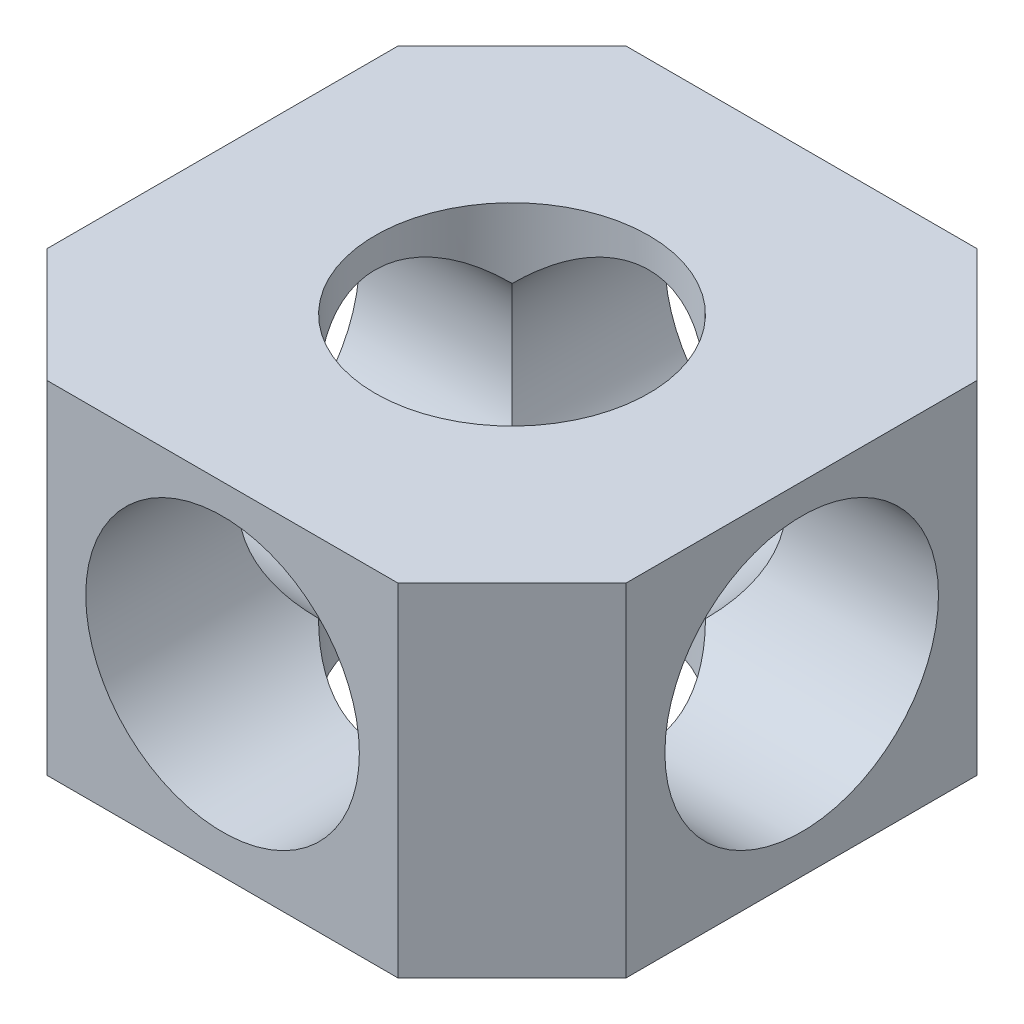
SolidWorks part; units mm, degrees
ref_plane "Front Plane" through (0, 0, 0) normal (0, 0, 1) x (1, 0, 0)
ref_plane "Top Plane" through (0, 0, 0) normal (0, 1, 0) x (1, 0, 0)
ref_plane "Right Plane" through (0, 0, 0) normal (1, 0, 0) x (0, 0, -1)
sketch "Sketch1" plane through (0, 0, 0) normal (0, 1, 0) x (1, 0, 0)
  line L1 (-5.6046, 5.0044) -> (2.862, 5.0044)
  line L2 (-5.6046, 5.0044) -> (-5.6046, -3.4623)
  line L3 (-5.6046, -3.4623) -> (2.862, -3.4623)
  line L4 (2.862, 5.0044) -> (2.862, -3.4623)
  line L5 (-5.6046, 5.0044) -> (2.862, -3.4623) construction
  line L6 (-5.6046, -3.4623) -> (2.862, 5.0044) construction
  point P0 (-1.3713, 0.7711)
  dimension "D1" = 8.4667
extrude "Boss-Extrude1" add sketch "Sketch1" along normal blind 5
chamfer "Chamfer1" distance 1.6667 4 edges at (-5.6046, 2.5, -5.0044) (2.862, 2.5, -5.0044) (-5.6046, 2.5, 3.4623) (2.862, 2.5, 3.4623)
sketch "Sketch2" plane through (2.862, 0, 0) normal (1, 0, 0) x (0, 0, -1)
  line L4 (-1.7956, 0) -> (3.3377, 0)
  line L5 (3.3377, 0) -> (3.3377, 5)
  line L6 (3.3377, 5) -> (-1.7956, 5)
  line L7 (-1.7956, 5) -> (-1.7956, 0)
  line L8 (-1.7956, 0) -> (3.3377, 0)
  line L9 (3.3377, 0) -> (3.3377, 5)
  line L10 (3.3377, 5) -> (-1.7956, 5)
  line L11 (-1.7956, 5) -> (-1.7956, 0)
  circle A0 centre (0.7727, 2.565) radius 2
  dimension "D4" = 4
  dimension "D2" = 2.565
  dimension "D3" = 2.565
  dimension "D1" = 0
extrude "Cut-Extrude1" cut sketch "Sketch2" against normal blind 10 contours A0
sketch "Sketch3" plane through (0, 0, 3.4623) normal (0, 0, 1) x (1, 0, 0)
  line L0 (1.1954, 0) -> (1.1954, 5) construction
  line L1 (-3.938, 0) -> (1.1954, 0) construction
  circle A0 centre (-1.3696, 2.565) radius 2
  dimension "D1" = 4
  dimension "D2" = 2.565
  dimension "D3" = 2.565
extrude "Cut-Extrude2" cut sketch "Sketch3" against normal through all
sketch "Sketch4" plane through (0, 5, 0) normal (0, 1, 0) x (1, 0, 0)
  line L0 (-3.938, -3.4623) -> (1.1954, -3.4623) construction
  line L1 (1.1954, 5.0044) -> (-3.938, 5.0044) construction
  line L2 (2.862, -1.7956) -> (2.862, 3.3377) construction
  circle A0 centre (-1.373, 0.7727) radius 2
  point P4 (0, 0)
  point P6 (13.5997, -5.4878)
  point P7 (-1.6828, 5.0044)
  dimension "D1" = 4
  dimension "D3" = 4.235
  dimension "D2" = 8.4667
extrude "Cut-Extrude3" cut sketch "Sketch4" against normal blind 10
